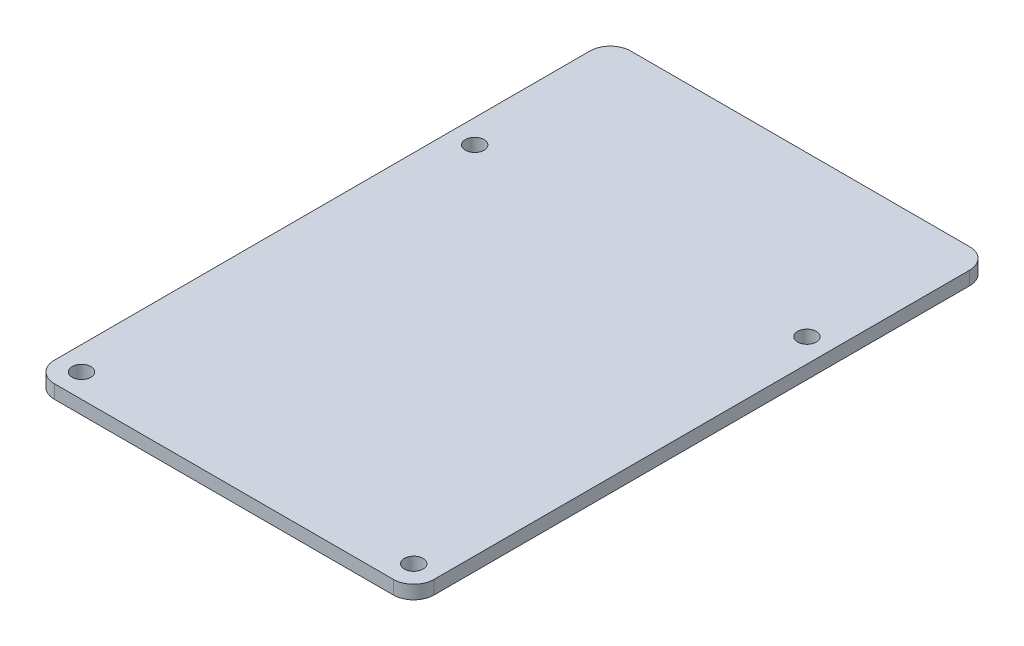
SolidWorks part; units mm, degrees
ref_plane "Front Plane" through (0, 0, 0) normal (0, 0, 1) x (1, 0, 0)
ref_plane "Top Plane" through (0, 0, 0) normal (0, 1, 0) x (1, 0, 0)
ref_plane "Right Plane" through (0, 0, 0) normal (1, 0, 0) x (0, 0, -1)
sketch "Sketch1" plane through (0, 0, 0) normal (0, 1, 0) x (1, 0, 0)
  line L1 (-28, -42.5) -> (28, -42.5)
  line L2 (-28, -42.5) -> (-28, 42.5)
  line L3 (-28, 42.5) -> (28, 42.5)
  line L4 (28, -42.5) -> (28, 42.5)
  line L5 (-28, -42.5) -> (28, 42.5) construction
  line L6 (-28, 42.5) -> (28, -42.5) construction
  circle A0 centre (-24.5, -39) radius 1.375
  circle A1 centre (-24.5, 19) radius 1.375
  circle A2 centre (24.5, 19) radius 1.375
  circle A3 centre (24.5, -39) radius 1.375
  point P0 (0, 0)
  point P14 (0, 0)
  point P15 (0, 0)
  point P16 (0, 0)
  point P17 (0, 0)
  point P18 (-24.5, -39)
  point P19 (-24.5, -39)
  point P20 (24.6696, -39)
  point P21 (0, 0)
  point P22 (0, 0)
  point P23 (16.7166, 19)
  dimension "D6" = 2.75
  dimension "D1" = 56
  dimension "D2" = 85
  dimension "D3" = 3.5
  dimension "D4" = 3.5
  dimension "D5" = 49
  dimension "D7" = 58
  dimension "D8" = 49
extrude "Boss-Extrude1" add sketch "Sketch1" along normal blind 2
fillet "Fillet1" radius 3 4 edges at (-28, 1, -42.5) (28, 1, -42.5) (28, 1, 42.5) (-28, 1, 42.5)
